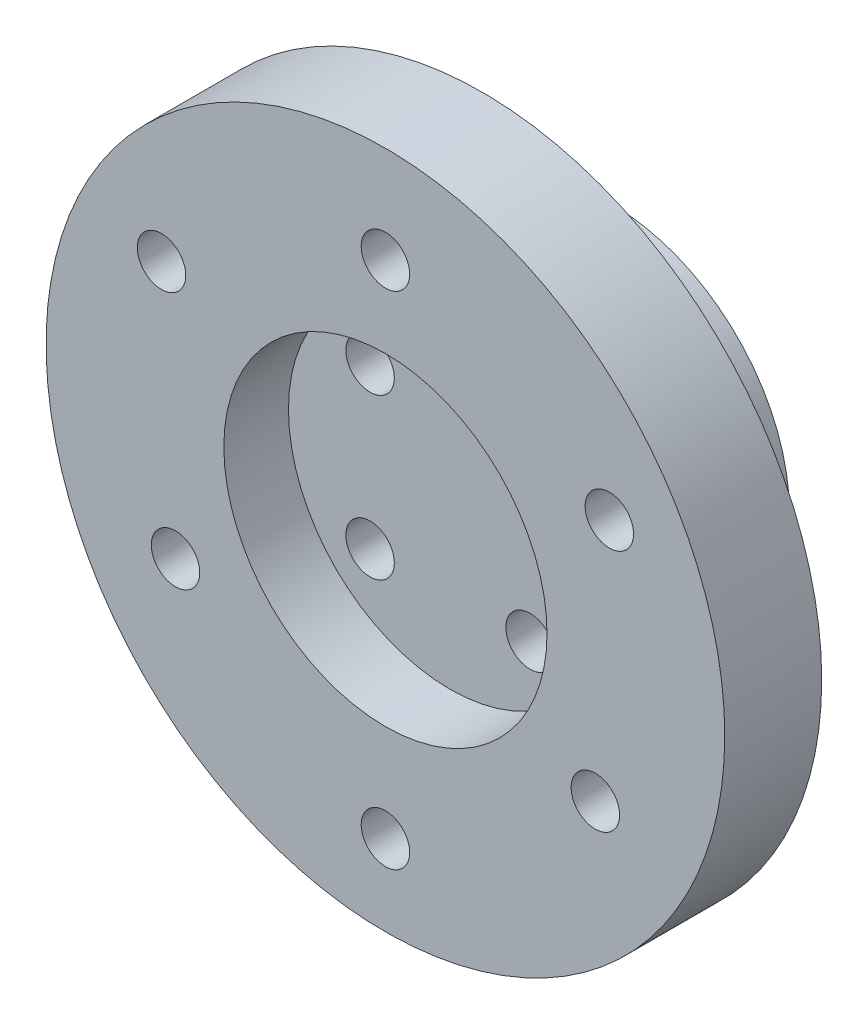
SolidWorks part; units mm, degrees
ref_plane "Front Plane" through (0, 0, 0) normal (0, 0, 1) x (1, 0, 0)
ref_plane "Top Plane" through (0, 0, 0) normal (0, 1, 0) x (1, 0, 0)
ref_plane "Right Plane" through (0, 0, 0) normal (1, 0, 0) x (0, 0, -1)
sketch "Sketch1" plane through (0, 0, 0) normal (0, 0, 1) x (1, 0, 0)
  circle A0 centre (0, 0) radius 21
  dimension "D1" = 42
extrude "Boss-Extrude1" add sketch "Sketch1" along normal blind 6 contours A0
sketch "Sketch6" plane through (0, 0, 0) normal (0, 0, -1) x (-1, 0, 0)
  line L0 (0, 0) -> (0, 15) construction
  line L1 (0, 0) -> (13.8564, 8) construction
  circle A0 centre (0, 15) radius 1.5
  circle A6 centre (12.9904, -7.5) radius 1.5
  circle A7 centre (-12.9904, -7.5) radius 1.5
  circle A8 centre (13.8564, 8) radius 1.5
  circle A9 centre (0, -16) radius 1.5
  circle A10 centre (-13.8564, 8) radius 1.5
  point P10 (0, 0)
  point P17 (3.2476, -1.875)
  point P19 (0, 0)
  dimension "D2" = 3
  dimension "D4" = 16
  dimension "D6" = 3
  dimension "D1" = 15
  dimension "D5" = 60
  dimension "D3" = 3
  dimension "D7" = 3
extrude "Cut-Extrude2" cut sketch "Sketch6" against normal blind 6
sketch "Sketch10" plane through (0, 0, 0) normal (0, 0, -1) x (-1, 0, 0)
  circle A0 centre (0, 0) radius 11
  dimension "D1" = 22
extrude "Boss-Extrude3" add sketch "Sketch10" along normal blind 8
sketch "Sketch8" plane through (0, 0, 0) normal (0, 0, -1) x (-1, 0, 0)
  line L0 (0, 0) -> (0, 10) construction
  line L1 (0, 0) -> (-4.9497, 4.9497) construction
  circle A4 centre (-4.9497, 4.9497) radius 1.5
  circle A8 centre (4.9497, 4.9497) radius 1.5
  circle A9 centre (4.9497, -4.9497) radius 1.5
  circle A10 centre (-4.9497, -4.9497) radius 1.5
  point P13 (0, 0)
  point P15 (2.1213, 0)
  point P16 (0, 0)
  dimension "D2" = 4
  dimension "D6" = 3
  dimension "D1" = 10
  dimension "D4" = 7
  dimension "D5" = 45
extrude "Cut-Extrude3" cut sketch "Sketch8" against normal mid plane 20
sketch "Sketch12" plane through (0, 0, 6) normal (0, 0, 1) x (1, 0, 0)
  circle A0 centre (0, 0) radius 10
  dimension "D1" = 20
extrude "Cut-Extrude5" cut sketch "Sketch12" against normal blind 4
sketch "Sketch13" plane through (0, 0, 0) normal (0, 0, -1) x (-1, 0, 0)
  circle A0 centre (-13.8564, 8) radius 3.5
  circle A1 centre (13.8564, 8) radius 3.5
  circle A2 centre (0, -16) radius 3.5
  point P9 (0, 0)
  dimension "D1" = 7
  dimension "D2" = 3
extrude "Cut-Extrude6" cut sketch "Sketch13" against normal blind 2.5
